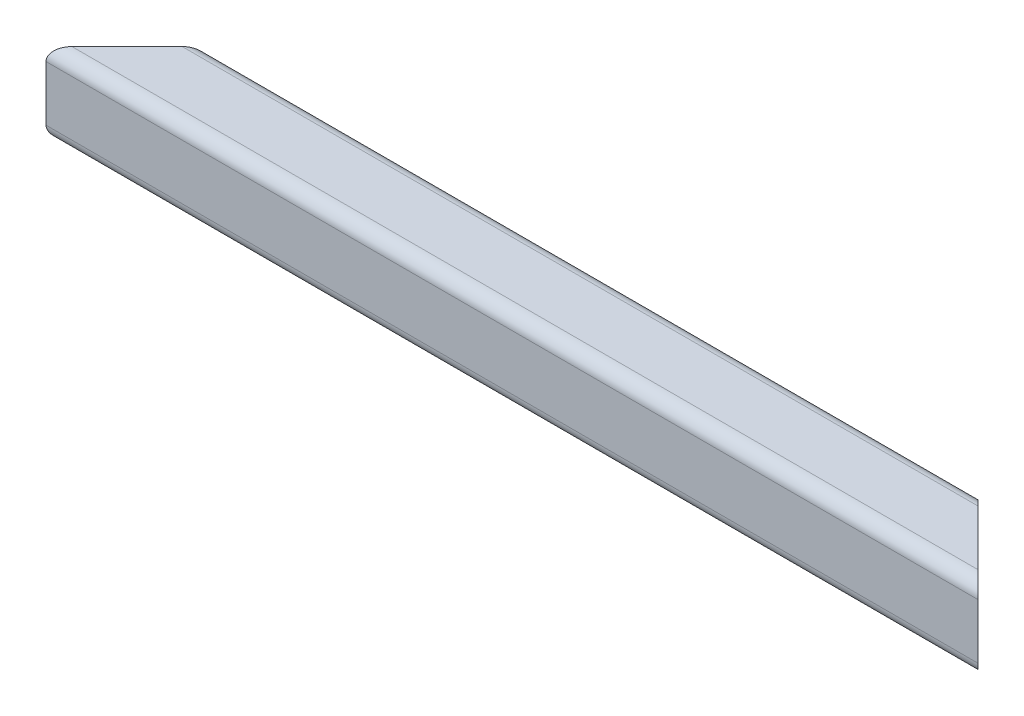
SolidWorks part; units mm, degrees
ref_plane "Front Plane" through (0, 0, 0) normal (0, 0, 1) x (1, 0, 0)
ref_plane "Top Plane" through (0, 0, 0) normal (0, 1, 0) x (1, 0, 0)
ref_plane "Right Plane" through (0, 0, 0) normal (1, 0, 0) x (0, 0, -1)
sketch "Sketch1" plane through (0, 0, 0) normal (0, 1, 0) x (1, 0, 0)
  line L0 (0, 0) -> (460, 0)
  dimension "D1" = 460
other "Tube (square) 40 X 40 X 3.2(9)"
ref_plane "Plane1" through (0, 0, 0) normal (1, 0, 0) x (0, 0, -1)
sketch "Sketch12" plane through (0, 0, 0) normal (1, 0, 0) x (0, 0, -1)
  line L0 (-13.6, -16.8) -> (13.6, -16.8)
  line L1 (-16.8, -13.6) -> (-16.8, 13.6)
  line L2 (13.6, 16.8) -> (-13.6, 16.8)
  line L3 (16.8, 13.6) -> (16.8, -13.6)
  line L4 (-13.6, -20) -> (13.6, -20)
  line L5 (-20, -13.6) -> (-20, 13.6)
  line L6 (13.6, 20) -> (-13.6, 20)
  line L7 (20, 13.6) -> (20, -13.6)
  line L8 (-20, 0) -> (-16.8, 0) construction
  line L9 (-16.8, 0) -> (16.8, 0) construction
  line L10 (16.8, 0) -> (20, 0) construction
  line L12 (0, 20) -> (0, 16.8) construction
  line L13 (0, 16.8) -> (0, -16.8) construction
  line L14 (0, -16.8) -> (0, -20) construction
  arc A0 (20, 13.6) -> (13.6, 20) centre (13.6, 13.6) ccw
  arc A1 (13.6, -20) -> (20, -13.6) centre (13.6, -13.6) ccw
  arc A2 (-20, -13.6) -> (-13.6, -20) centre (-13.6, -13.6) ccw
  arc A3 (-13.6, 20) -> (-20, 13.6) centre (-13.6, 13.6) ccw
  arc A4 (-13.6, 16.8) -> (-16.8, 13.6) centre (-13.6, 13.6) ccw
  arc A5 (16.8, 13.6) -> (13.6, 16.8) centre (13.6, 13.6) ccw
  arc A6 (13.6, -16.8) -> (16.8, -13.6) centre (13.6, -13.6) ccw
  arc A7 (-16.8, -13.6) -> (-13.6, -16.8) centre (-13.6, -13.6) ccw
  point P2 (-20, 20)
  point P33 (-20, -20)
  point P34 (20, -20)
  point P36 (20, 20)
  point P37 (0, 0)
  dimension "D1" = 6.4
  dimension "Thickness" = 3.2
  dimension "V_leg" = 40
  dimension "H_leg" = 40
ref_plane "Plane2" through (0, 20, 0) normal (0, 1, 0) x (1, 0, 0)
sketch "Sketch13" plane through (0, 20, 0) normal (0, 1, 0) x (1, 0, 0)
  line L1 (0, 13.6) -> (0, -13.6) construction
  line L3 (460, 20) -> (460, -20)
  line L4 (0, 20) -> (0, 13.6)
  line L5 (0, 13.6) -> (460, 13.6)
  line L6 (460, 13.6) -> (460, 20)
  line L7 (460, 20) -> (0, 20)
  line L11 (460, 20) -> (420, 20)
  line L12 (0, 20) -> (0, -20)
  line L13 (40, 20) -> (0, -20)
  line L20 (40, 20) -> (0, 20)
  line L23 (420, 20) -> (460, -20)
  dimension "D2" = 40
  dimension "D1" = 0
extrude "Cut-Extrude1" cut sketch "Sketch13" against normal through all
sketch "Sketch15" plane through (0, 0, 0) normal (0, 1, 0) x (1, 0, 0)
  line L0 (20, 0) -> (440, 0) construction
  line L4 (426.4, 13.6) -> (33.6, 13.6)
  line L5 (33.6, 13.6) -> (6.4, -13.6)
  line L6 (6.4, -13.6) -> (453.6, -13.6)
  line L7 (453.6, -13.6) -> (426.4, 13.6)
  line L8 (426.4, 13.6) -> (33.6, 13.6) construction
  line L9 (33.6, 13.6) -> (6.4, -13.6) construction
  line L10 (6.4, -13.6) -> (453.6, -13.6) construction
  line L11 (453.6, -13.6) -> (426.4, 13.6) construction
  circle A0 centre (440, 0) radius 2
  circle A1 centre (230, 0) radius 2
  circle A2 centre (20, 0) radius 2
  dimension "D1" = 0
extrude "Cut-Extrude4" cut sketch "Sketch15" against normal through all
